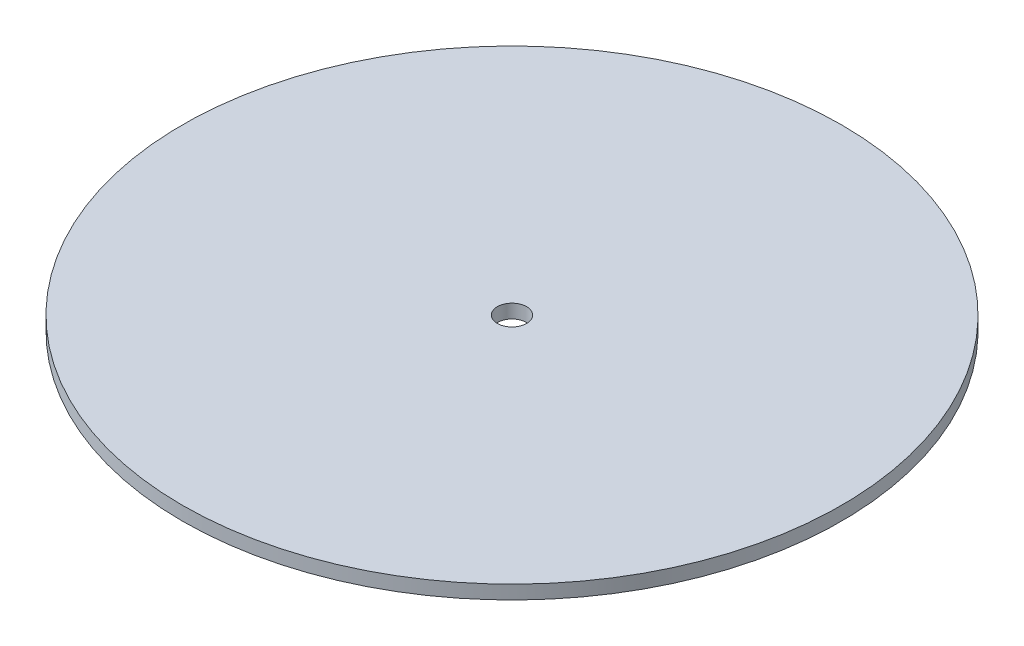
SolidWorks part; units mm, degrees
ref_plane "Front Plane" through (0, 0, 0) normal (0, 0, 1) x (1, 0, 0)
ref_plane "Top Plane" through (0, 0, 0) normal (0, 1, 0) x (1, 0, 0)
ref_plane "Right Plane" through (0, 0, 0) normal (1, 0, 0) x (0, 0, -1)
sketch "Sketch1" plane through (0, 0, 0) normal (0, 1, 0) x (1, 0, 0)
  circle A0 centre (0, 0) radius 76.2
  dimension "D1" = 152.4
extrude "Boss-Extrude1" add sketch "Sketch1" along normal blind 3.175
hole_wizard "1/4 Clearance Hole1" positions "Sketch2" profile "Sketch4" hole size "1/4" standard "ANSI Inch" end condition through all
sketch "Sketch2" plane through (0, 3.175, 0) normal (0, 1, 0) x (1, 0, 0)
  point P0 (0, 0)
sketch "Sketch4" plane through (0, 3.175, 0) normal (1, 0, 0) x (0, 0, 1)
  line L0 (0, 0) -> (0, 3.175)
  line L1 (0, 3.175) -> (3.3782, 3.175)
  line L2 (3.3782, 3.175) -> (3.3782, 0)
  line L5 (3.3782, 0) -> (0, 0)
  line L11 (0, -6.35) -> (0, 107.95) construction
  dimension "Thru Hole Dia." = 6.7564
  dimension "Thru Hole Depth" = 3.175
equation "\"airframeInnerDiameter\"= 6in"
equation "\"outerDiameter\"= 6.112in"
equation "\"airframeBulkheadThickness\"= 0.125in"
equation "\"payloadAirframeLength\"= 10in"
equation "\"payloadInnerDiameter\"= 6in - 0.056in"
equation "\"payloadOuterDiameter\"= \"airframeInnerDiameter\""
equation "\"payloadLength\"= 11in"
equation "\"payloadBand\"= 2in"
equation "\"payloadOffsetFromAft\"= 6in"
equation "\"upperAirframeLength\"= 25in"
equation "\"recoveryBayInnerDiameter\"= 5.888in"
equation "\"recoveryLength\"= 8in"
equation "\"recoveryBand\"= 2in"
equation "\"recoveryCouplerOuter\"=\"airframeInnerDiameter\""
equation "\"recoveryOffsetFromAft\"= 3in"
equation "\"midAirframeLength\"= 20in"
equation "\"atsLength\"= 11in"
equation "\"atsInner\"= 5.888in"
equation "\"atsBand\"= 2in"
equation "\"atsCouplerOuter\"=\"airframeInnerDiameter\""
equation "\"atsOffsetFromAft\"= 3in"
equation "\"lowerAirframeLength\"= 40in"
equation "\"motorTubeOuterDiameter\"= 4.25in"
equation "\"motorTubeInnerDiameter\"= 4in"
equation "\"motorTubeLength\"= 32in"
equation "\"centeringRingOuterDiameter\"= \"airframeInnerDiameter\""
equation "\"centeringRingInnerDiameter\"= \"motorTubeOuterDiameter\""
equation "\"centeringRingThickness\"= 0.375in"
equation "\"topCenteringRingOffsetFromAft\"= 16.7in"
equation "\"bottomCenteringRingOffsetFromAft\"= 0.3in"
equation "\"finSlotLength\"= 8in"
equation "\"finSlotOffsetFromAft\"= 3in"
equation "\"finSlotWidth\"= 0.187in"
equation "\"motorCasingOuterDiameter\"= 3in"
equation "\"motorCasingCenteringRingThickness\"= 0.25in"
equation "\"D1@Sketch1\"=\"airframeInnerDiameter\""
equation "\"D1@Boss-Extrude1\"=\"airframeBulkheadThickness\""
